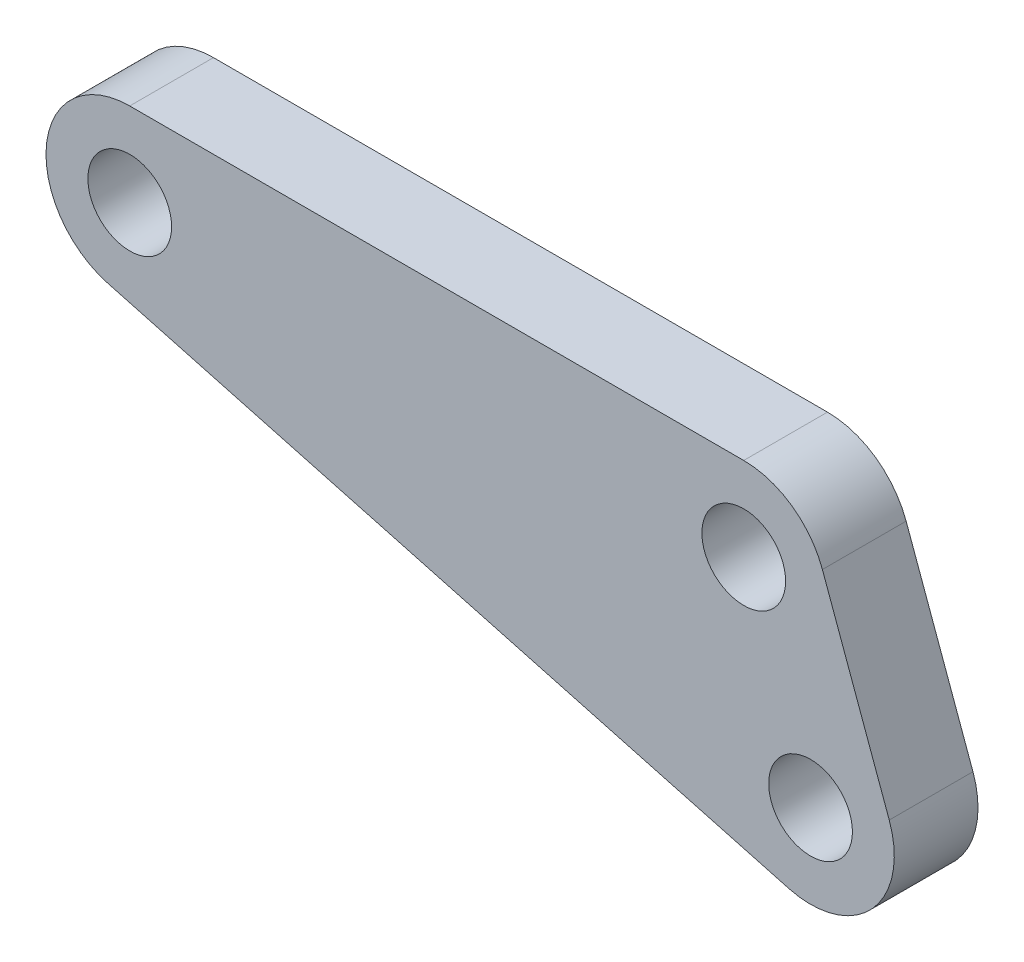
SolidWorks part; units mm, degrees
ref_plane "Front Plane" through (0, 0, 0) normal (0, 0, 1) x (1, 0, 0)
ref_plane "Top Plane" through (0, 0, 0) normal (0, 1, 0) x (1, 0, 0)
ref_plane "Right Plane" through (0, 0, 0) normal (1, 0, 0) x (0, 0, -1)
sketch "Sketch1" plane through (0, 0, 0) normal (0, 0, 1) x (1, 0, 0)
  line L0 (0, 0) -> (-22, 0)
  line L1 (0, 0) -> (2.3941, -6.5778)
  dimension "D1" = 22
  dimension "D2" = 7
  dimension "D3" = 110
sketch "Sketch2" plane through (0, 0, 0) normal (0, 0, 1) x (1, 0, 0)
  line L0 (-22, 3) -> (0, 3)
  line L1 (2.8191, 1.0261) -> (5.2132, -5.5518)
  line L2 (1.6131, -9.4744) -> (-22.781, -2.8965)
  circle A0 centre (-22, 0) radius 1.5
  arc A1 (-22, 3) -> (-22.781, -2.8965) centre (-22, 0) ccw
  circle A2 centre (0, 0) radius 1.5
  arc A3 (2.8191, 1.0261) -> (0, 3) centre (0, 0) ccw
  circle A4 centre (2.3941, -6.5778) radius 1.5
  arc A5 (1.6131, -9.4744) -> (5.2132, -5.5518) centre (2.3941, -6.5778) ccw
  dimension "D1" = 3
  dimension "D2" = 6
  dimension "D3" = 3
  dimension "D4" = 6
  dimension "D5" = 3
  dimension "D6" = 6
extrude "Boss-Extrude1" add sketch "Sketch2" along normal blind 3
